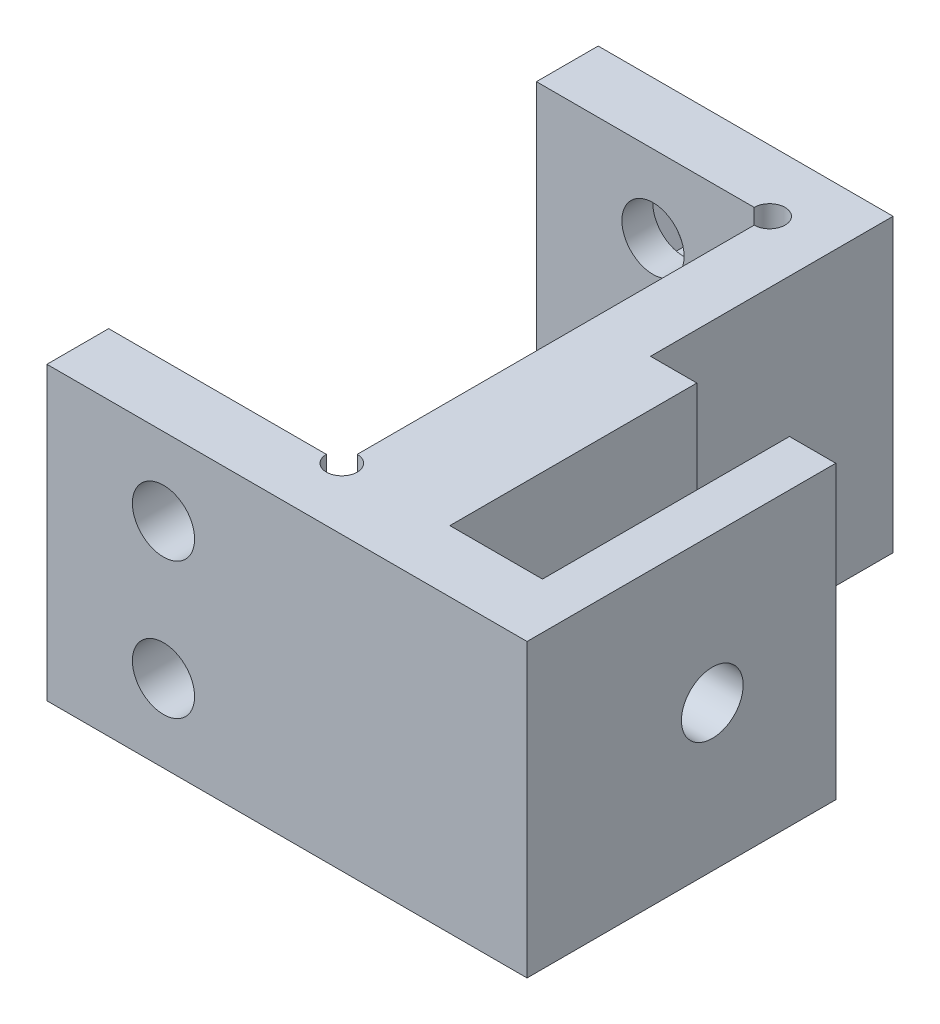
SolidWorks part; units mm, degrees
ref_plane "Front" through (0, 0, 0) normal (0, 0, 1) x (1, 0, 0)
ref_plane "Top" through (0, 0, 0) normal (0, 1, 0) x (1, 0, 0)
ref_plane "Right" through (0, 0, 0) normal (1, 0, 0) x (0, 0, -1)
sketch "Sketch1" plane through (0, 0, 0) normal (0, 0, 1) x (1, 0, 0)
  line L1 (0, 0) -> (11.9888, 0)
  line L2 (0, 0) -> (0, 14.986)
  line L3 (0, 14.986) -> (11.9888, 14.986)
  line L4 (11.9888, 0) -> (11.9888, 14.986)
  dimension "D1" = 14.986
  dimension "D2" = 11.9888
extrude "Boss-Extrude1" add sketch "Sketch1" along normal blind 3.175
sketch "Sketch6" plane through (11.9888, 0, 0) normal (1, 0, 0) x (0, 0, -1)
  line L0 (0, 0) -> (0, 14.986) construction
  line L1 (0, 0) -> (-25.1714, 0)
  line L2 (0, 0) -> (0, 14.986)
  line L3 (0, 14.986) -> (-25.1714, 14.986)
  line L4 (-25.1714, 0) -> (-25.1714, 14.986)
  line L5 (-3.175, 14.986) -> (0, 14.986) construction
  line L6 (-3.175, 0) -> (-3.175, 14.986) construction
  dimension "D1" = 21.9964
extrude "Boss-Extrude6" add sketch "Sketch6" along normal blind 3.175
sketch "Sketch10" plane through (0, 0, 25.1714) normal (0, 0, 1) x (1, 0, 0)
  line L0 (11.9888, 14.986) -> (0, 14.986) construction
  line L1 (24.6888, 14.986) -> (0, 14.986)
  line L2 (24.6888, 14.986) -> (24.6888, 0)
  line L3 (24.6888, 0) -> (0, 0)
  line L4 (0, 14.986) -> (0, 0)
  line L5 (11.9888, 0) -> (11.9888, 14.986) construction
  dimension "D1" = 12.7
extrude "Boss-Extrude7" add sketch "Sketch10" along normal blind 3.175
ref_plane "Plane2" through (19.9263, 0, 0) normal (1, 0, 0) x (0, 0, -1)
hole_wizard "M3 Clearance Hole1" positions "Sketch3" profile "Sketch2" hole size "M3" standard "Ansi Metric" end condition through all
sketch "Sketch3" plane through (-0.0898, -1.1144, 0) normal (0, 0, 1) x (1, 0, 0)
  line L8 (6.0842, 8.6074) -> (6.0842, 12.1126) construction
  line L10 (6.0842, 8.6074) -> (6.0842, 5.1022) construction
  line L12 (0.0898, 8.6074) -> (12.0786, 8.6074) construction
  line L14 (12.0786, 1.1144) -> (12.0786, 16.1004) construction
  line L15 (0.0898, 16.1004) -> (0.0898, 1.1144) construction
  point P0 (6.0842, 12.1126)
  point P1 (6.0842, 5.1022)
  dimension "D1" = 7.0104
sketch "Sketch2" plane through (5.9944, 10.9982, 0) normal (1, 0, 0) x (0, 1, 0)
  line L0 (0, 0) -> (0, 28.3464)
  line L1 (0, 28.3464) -> (1.6, 28.3464)
  line L2 (1.6, 28.3464) -> (1.6, 0)
  line L5 (1.6, 0) -> (0, 0)
  line L11 (0, -6.35) -> (0, 107.95) construction
  dimension "Thru Hole Dia." = 3.2
  dimension "Thru Hole Depth" = 28.3464
sketch "Sketch15" plane through (0, 0, 0) normal (0, -1, 0) x (1, 0, 0)
  circle A0 centre (11.9888, 25.1714) radius 0.7937
  circle A1 centre (11.9888, 3.175) radius 0.7937
  dimension "D1" = 1.5875
extrude "Cut-Extrude5" cut sketch "Sketch15" against normal through all
sketch "Sketch16" plane through (0, 0, 0) normal (0, 0, -1) x (-1, 0, 0)
  line L0 (-5.9944, 3.9878) -> (-5.9944, 6.7378) construction
  line L1 (-4.4067, 6.7378) -> (-7.5821, 6.7378)
  line L2 (-2.819, 3.9878) -> (-4.4067, 6.7378)
  line L3 (-5.9944, 3.9878) -> (-8.376, 5.3628) construction
  line L4 (-4.4067, 1.2378) -> (-2.819, 3.9878)
  line L5 (-5.9944, 10.9982) -> (-5.9944, 13.7482) construction
  line L6 (-7.5821, 1.2378) -> (-4.4067, 1.2378)
  line L7 (-4.4067, 13.7482) -> (-7.5821, 13.7482)
  line L8 (-9.1698, 3.9878) -> (-7.5821, 1.2378)
  line L9 (-2.819, 10.9982) -> (-4.4067, 13.7482)
  line L10 (-7.5821, 6.7378) -> (-9.1698, 3.9878)
  line L11 (-4.4067, 8.2482) -> (-2.819, 10.9982)
  line L12 (-5.9944, 3.9878) -> (-3.6128, 5.3628) construction
  line L13 (-5.9944, 3.9878) -> (-3.6128, 2.6128) construction
  line L14 (-5.9944, 3.9878) -> (-5.9944, 1.2378) construction
  line L15 (-5.9944, 3.9878) -> (-8.376, 2.6128) construction
  line L16 (-5.9944, 3.9878) -> (-8.376, 5.3628) construction
  line L17 (-7.5821, 8.2482) -> (-4.4067, 8.2482)
  line L18 (-9.1698, 10.9982) -> (-7.5821, 8.2482)
  line L19 (-7.5821, 13.7482) -> (-9.1698, 10.9982)
  line L20 (-5.9944, 10.9982) -> (-8.376, 12.3732) construction
  dimension "D2" = 5.5
  dimension "D4" = 5.5
  dimension "D1" = 6
  dimension "D3" = 6
extrude "Cut-Extrude6" cut sketch "Sketch16" against normal blind 1.5875
sketch "Sketch17" plane through (0, 0, 25.1714) normal (0, 0, -1) x (-1, 0, 0)
  line L1 (-15.1638, 0) -> (-24.6888, 0)
  line L2 (-15.1638, 0) -> (-15.1638, 14.986)
  line L3 (-15.1638, 14.986) -> (-24.6888, 14.986)
  line L4 (-24.6888, 0) -> (-24.6888, 14.986)
extrude "Boss-Extrude8" add sketch "Sketch17" along normal blind 12.7
ref_plane "Plane3" through (19.9263, 0, 0) normal (1, 0, 0) x (0, 0, -1)
sketch "Sketch19" plane through (19.9263, 0, 0) normal (1, 0, 0) x (0, 0, -1)
  line L0 (-18.3693, 14.986) -> (-18.3693, 0) construction
  line L1 (-28.3464, 14.986) -> (-12.4714, 14.986) construction
  line L2 (-28.3464, 0) -> (-12.4714, 0) construction
  line L3 (-25.1714, 14.986) -> (-25.1714, 0)
  line L4 (-25.1714, 14.986) -> (-12.4714, 14.986)
  line L5 (-12.4714, 14.986) -> (-12.4714, 0)
  line L6 (-12.4714, 0) -> (-25.1714, 0)
  circle A0 centre (-18.3693, 7.493) radius 6.35 construction
  dimension "D1" = 12.7
extrude "Cut-Extrude7" cut sketch "Sketch19" against normal blind 2.3813 and the other way blind 2.3813
sketch "Sketch20" plane through (24.6888, 0, 0) normal (1, 0, 0) x (0, 0, -1)
  line L0 (-18.8214, 14.986) -> (-18.8214, 0) construction
  line L1 (-12.4714, 14.986) -> (-25.1714, 14.986) construction
  line L2 (-28.3464, 0) -> (-12.4714, 0) construction
  circle A0 centre (-18.8214, 7.493) radius 1.5875
  dimension "D1" = 3.175
extrude "Cut-Extrude8" cut sketch "Sketch20" against normal blind 16.6053
sketch "Sketch21" plane through (11.9888, 0, 0) normal (-1, 0, 0) x (0, 0, 1)
  line L0 (18.8214, 7.493) -> (22.4876, 7.493) construction
  line L1 (22.4876, 7.493) -> (20.6545, 10.668)
  line L2 (20.6545, 10.668) -> (16.9883, 10.668)
  line L3 (16.9883, 10.668) -> (15.1552, 7.493)
  line L4 (15.1552, 7.493) -> (16.9883, 4.318)
  line L5 (16.9883, 4.318) -> (20.6545, 4.318)
  line L6 (20.6545, 4.318) -> (22.4876, 7.493)
  line L7 (16.9883, 10.668) -> (18.8214, 7.493) construction
  line L8 (18.8214, 7.493) -> (16.9883, 4.318) construction
  line L9 (16.9883, 10.668) -> (16.9883, 4.318) construction
  line L10 (22.4876, 7.493) -> (16.9883, 4.318) construction
  line L11 (20.6545, 10.668) -> (18.8214, 7.493) construction
  dimension "D1" = 6.35
extrude "Cut-Extrude9" cut sketch "Sketch21" against normal blind 3.3973
